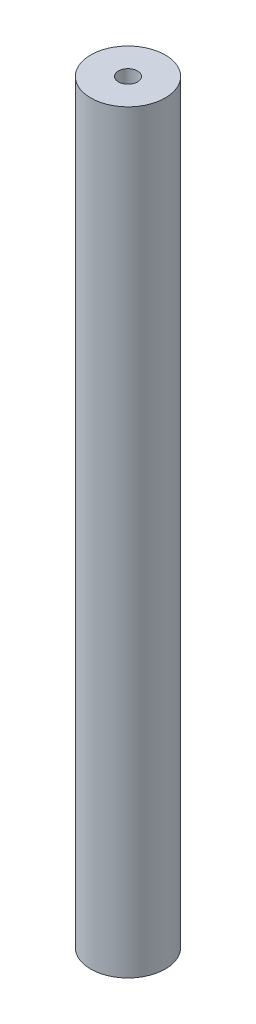
SolidWorks part; units mm, degrees
material "Polyetheretherketone (PEEK)"
ref_plane "Front Plane" through (0, 0, 0) normal (0, 0, 1) x (1, 0, 0)
ref_plane "Top Plane" through (0, 0, 0) normal (0, 1, 0) x (1, 0, 0)
ref_plane "Right Plane" through (0, 0, 0) normal (1, 0, 0) x (0, 0, -1)
sketch "Sketch2" plane through (0, 0, 0) normal (0, 1, 0) x (1, 0, 0)
  circle A0 centre (0, 0) radius 8.2
  dimension "D1" = 16.4
extrude "Boss-Extrude1" add sketch "Sketch2" along normal blind 166
sketch "Sketch3" plane through (0, 166, 0) normal (0, 1, 0) x (1, 0, 0)
  circle A0 centre (0, 0) radius 2.1
  circle A1 centre (0, 0) radius 8.2 construction
  dimension "D1" = 4.2
extrude "Cut-Extrude1" cut sketch "Sketch3" against normal blind 10
sketch "Sketch4" plane through (0, 0, 0) normal (0, -1, 0) x (1, 0, 0)
  circle A0 centre (0, 0) radius 2.1
  circle A1 centre (0, 0) radius 8.2 construction
  dimension "D1" = 4.2
extrude "Cut-Extrude2" cut sketch "Sketch4" against normal blind 10
